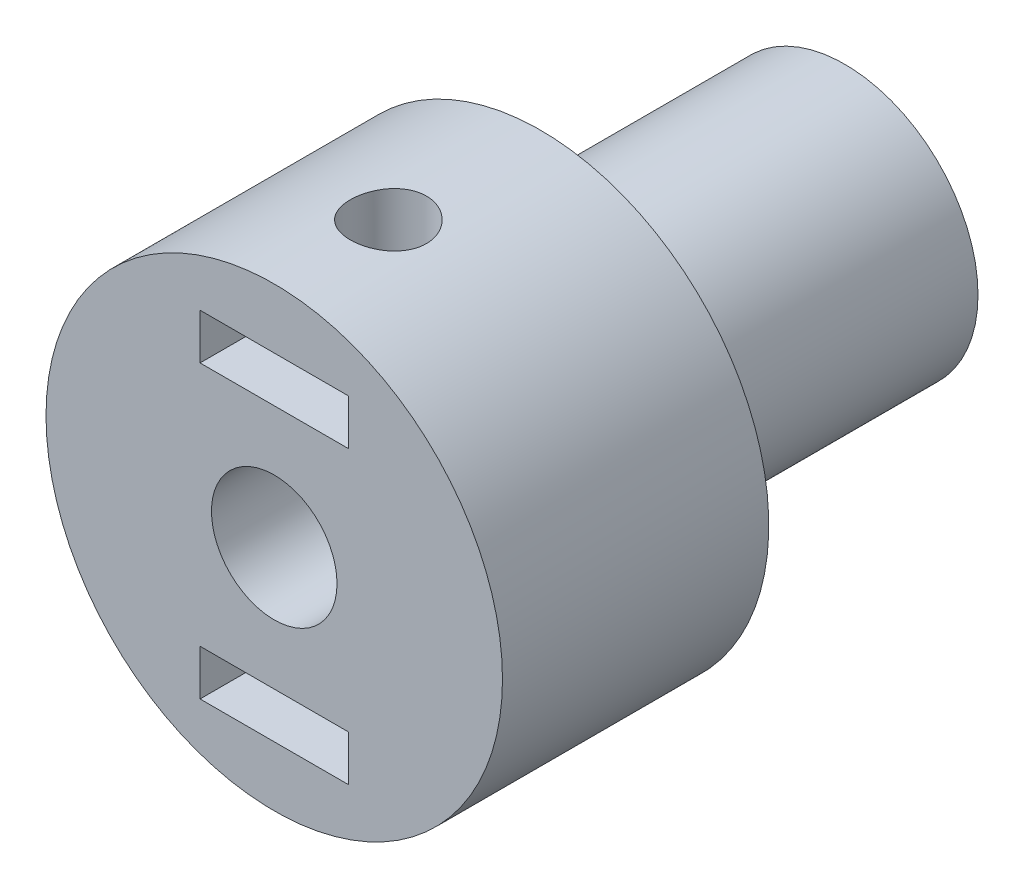
SolidWorks part; units mm, degrees
ref_plane "Front Plane" through (0, 0, 0) normal (0, 0, 1) x (1, 0, 0)
ref_plane "Top Plane" through (0, 0, 0) normal (0, 1, 0) x (1, 0, 0)
ref_plane "Right Plane" through (0, 0, 0) normal (1, 0, 0) x (0, 0, -1)
sketch "Sketch1" plane through (0, 0, 0) normal (0, 0, 1) x (1, 0, 0)
  circle A0 centre (0, 0) radius 6
  dimension "D1" = 12
extrude "Boss-Extrude1" add sketch "Sketch1" along normal blind 15
sketch "Sketch2" plane through (0, 0, 15) normal (0, 0, 1) x (1, 0, 0)
  circle A0 centre (0, 0) radius 1.65
  dimension "D1" = 3.3
extrude "Cut-Extrude1" cut sketch "Sketch2" against normal through all
sketch "Sketch4" plane through (0, 0, 0) normal (0, 1, 0) x (1, 0, 0)
  line L0 (6, 0) -> (-6, 0) construction
  line L1 (-6, -15) -> (6, -15) construction
  circle A0 centre (0, -3) radius 1
  circle A1 centre (0, -12) radius 1
  dimension "D1" = 2
  dimension "D2" = 2
  dimension "D3" = 3
  dimension "D4" = 3
ref_plane "Plane1" through (0, 6, 0) normal (0, 1, 0) x (1, 0, 0)
ref_plane "Plane4" through (0, 0, 7.5) normal (0, 0, 1) x (1, 0, 0)
sketch "Sketch13" plane through (0, 0, 15) normal (0, 0, 1) x (1, 0, 0)
  line L0 (0, 6) -> (0, 1.65) construction
  line L2 (-1.95, 4.425) -> (1.95, 4.425)
  line L3 (-1.95, 4.425) -> (-1.95, 3.225)
  line L4 (-1.95, 3.225) -> (1.95, 3.225)
  line L5 (1.95, 4.425) -> (1.95, 3.225)
  line L6 (-1.95, 4.425) -> (1.95, 3.225) construction
  line L7 (-1.95, 3.225) -> (1.95, 4.425) construction
  circle A1 centre (0, 0) radius 6 construction
  circle A2 centre (0, 0) radius 1.65 construction
  point P0 (0, 3.825)
  dimension "D1" = 3.9
  dimension "D2" = 1.2
extrude "Cut-Extrude6" cut sketch "Sketch13" against normal blind 4.95
extrude "Cut-Extrude7" cut sketch "Sketch4" against normal mid plane 15 contours A1
sketch "Sketch19" plane through (0, 0, 0) normal (0, 0, -1) x (-1, 0, 0)
  circle A0 centre (0, 0) radius 3.5
  circle A1 centre (0, 0) radius 5.5
  circle A2 centre (0, 0) radius 6
  circle M2 centre (0, 0) radius 6
  dimension "D1" = 7
  dimension "D2" = 11
sketch "Sketch20" plane through (0, 0, 15) normal (0, 0, 1) x (1, 0, 0)
  line L0 (-6, 0) -> (6, 0) construction
  circle A1 centre (0, 0) radius 6 construction
mirror "Mirror1" about plane through (0, 0, 0) normal (0, 1, 0) of "Cut-Extrude6"
extrude "Cut-Extrude12" cut sketch "Sketch19" against normal blind 8 contours A1 A0 | A1 M2
ref_plane "Plane5" through (0, 0, 6) normal (0, 0, -1) x (-1, 0, 0)
